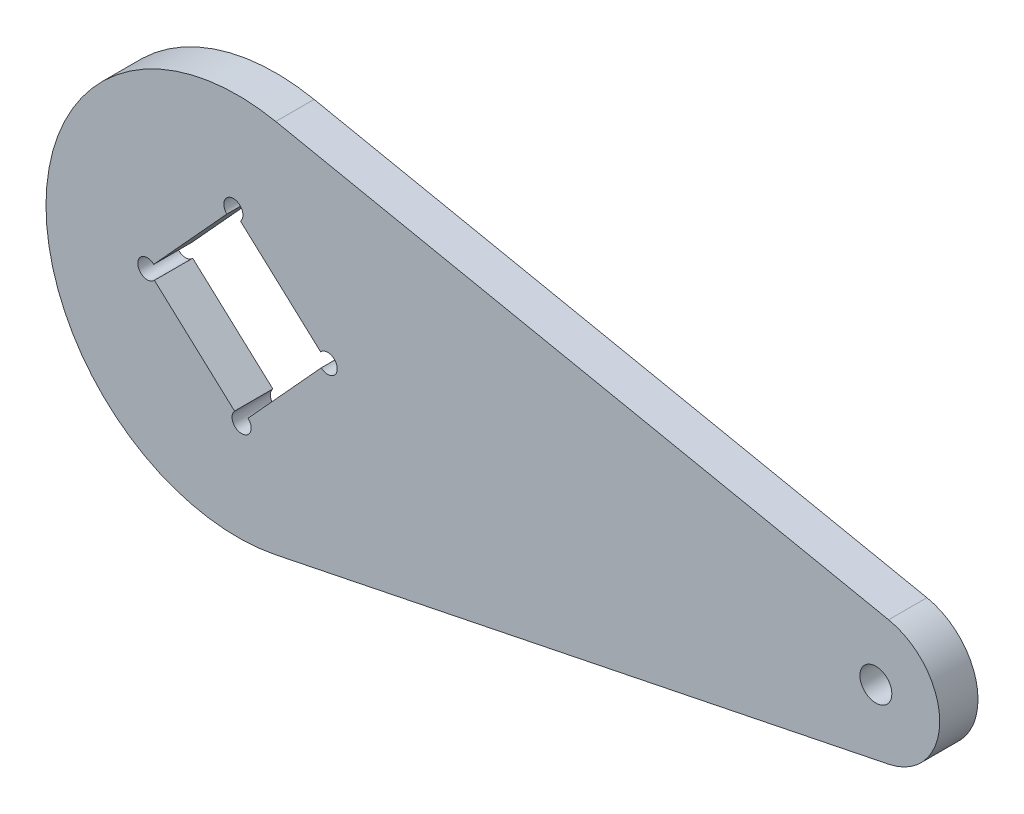
SolidWorks part; units mm, degrees
ref_plane "前视基准面" through (0, 0, 0) normal (0, 0, 1) x (1, 0, 0)
ref_plane "上视基准面" through (0, 0, 0) normal (0, 1, 0) x (1, 0, 0)
ref_plane "右视基准面" through (0, 0, 0) normal (1, 0, 0) x (0, 0, -1)
sketch "草图1" plane through (0, 0, 0) normal (0, 0, 1) x (1, 0, 0)
  line L0 (6, -29.3939) -> (102, -9.798)
  line L1 (-14.1274, -0.6465) -> (-0.6465, 14.1274)
  line L2 (-14.1274, -0.6465) -> (0.6465, -14.1274)
  line L3 (0.6465, -14.1274) -> (14.1274, 0.6465)
  line L4 (-0.6465, 14.1274) -> (14.1274, 0.6465)
  line L5 (-14.1274, -0.6465) -> (14.1274, 0.6465) construction
  line L6 (0.6465, -14.1274) -> (-0.6465, 14.1274) construction
  line L7 (6, 29.3939) -> (102, 9.798)
  line L8 (-1000, 0) -> (49000, 0) construction
  circle A0 centre (-14.1274, -0.6465) radius 1.5
  circle A1 centre (-0.6465, 14.1274) radius 1.5
  circle A2 centre (14.1274, 0.6465) radius 1.5
  circle A3 centre (0.6465, -14.1274) radius 1.5
  circle A4 centre (100, 0) radius 2.5
  arc A5 (6, 29.3939) -> (6, -29.3939) centre (0, 0) ccw
  arc A6 (102, -9.798) -> (102, 9.798) centre (100, 0) ccw
  point P0 (0, 0)
  dimension "D2" = 3
  dimension "D3" = 3
  dimension "D4" = 3
  dimension "D5" = 3
  dimension "D6" = 5
  dimension "D8" = 60
  dimension "D9" = 20
  dimension "D1" = 20
  dimension "D7" = 100
  dimension "D10" = 47.62
extrude "凸台-拉伸1" add sketch "草图1" along normal blind 6 contours L0 A6 L7 A5 A3 L2 A0 L1 A1 L4 A2 L3 A4
